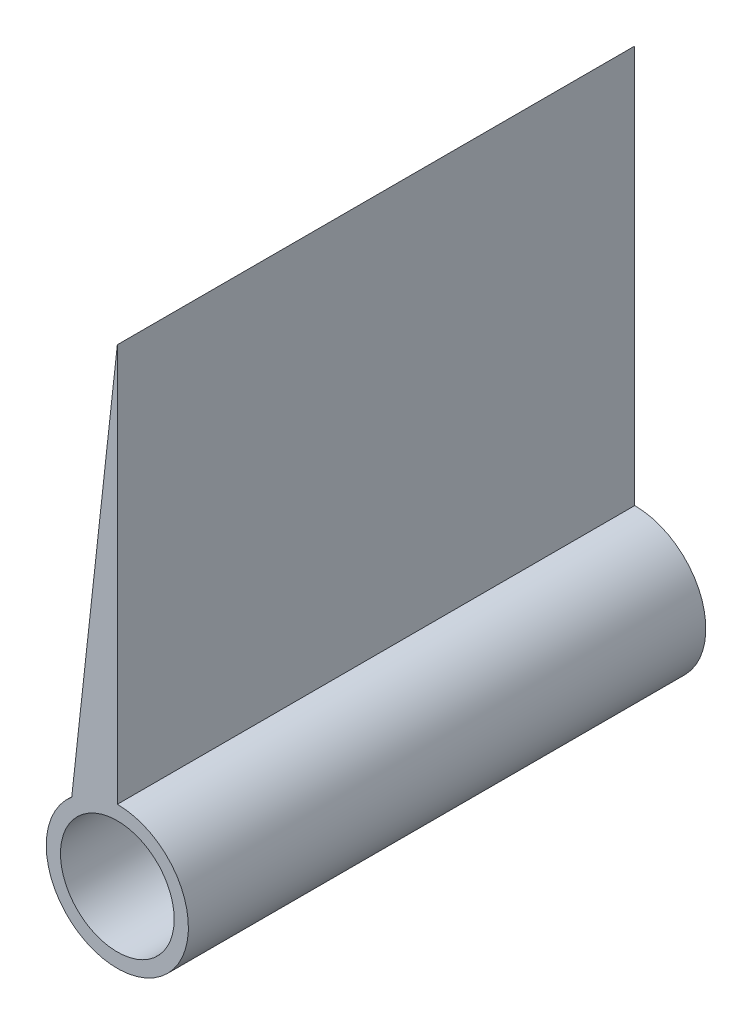
SolidWorks part; units mm, degrees
ref_plane "Front Plane" through (0, 0, 0) normal (0, 0, 1) x (1, 0, 0)
ref_plane "Top Plane" through (0, 0, 0) normal (0, 1, 0) x (1, 0, 0)
ref_plane "Right Plane" through (0, 0, 0) normal (1, 0, 0) x (0, 0, -1)
sketch "Sketch1" plane through (0, 0, 0) normal (0, 0, 1) x (1, 0, 0)
  circle A0 centre (0, 0) radius 5
  circle A1 centre (0, 0) radius 6.25
  dimension "D1" = 10
  dimension "D2" = 1.25
extrude "Boss-Extrude1" add sketch "Sketch1" along normal blind 45.5
sketch "Sketch6" plane through (0, 0, 0) normal (0, 0, 1) x (1, 0, 0)
  line L0 (0, 6.25) -> (0, 41.25)
  line L1 (0, 41.25) -> (-4.0082, 4.7955)
  circle A0 centre (0, 0) radius 6.25 construction
  arc A1 (0, 6.25) -> (-4.0082, 4.7955) centre (0, 0) ccw
  dimension "D1" = 36.4545
  dimension "D2" = 35
extrude "Boss-Extrude4" add sketch "Sketch6" along normal up to surface (45.5 mm away) up to face at (6.25, 0, 45.5)
